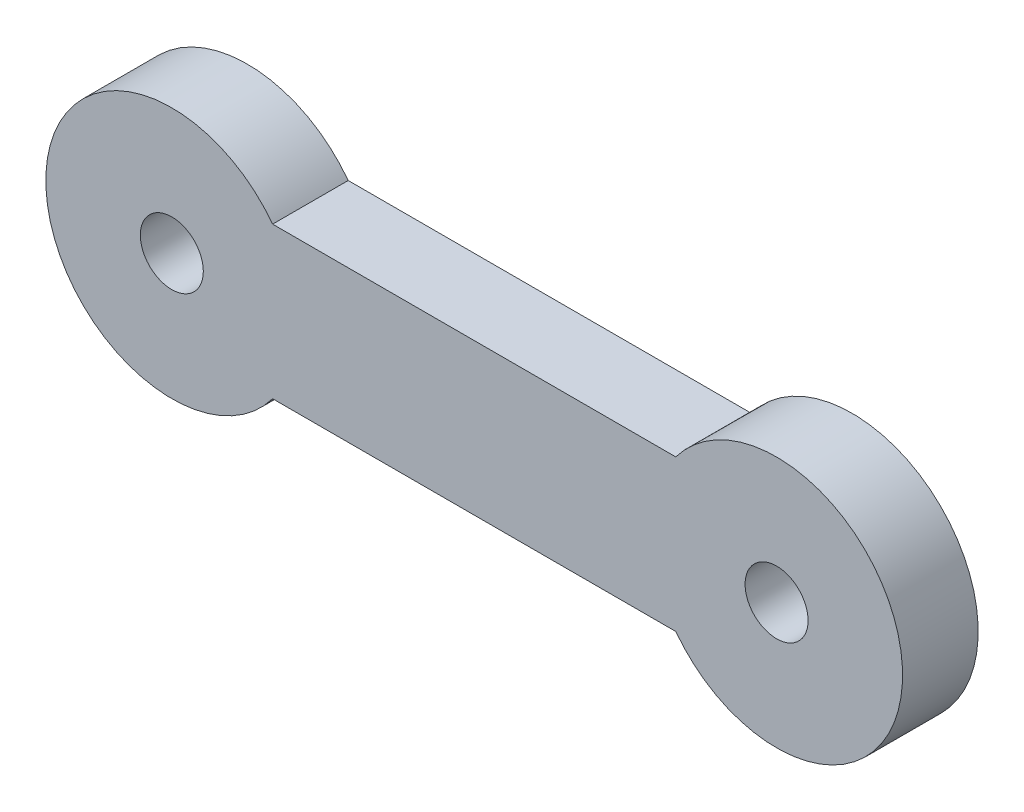
SolidWorks part; units mm, degrees
ref_plane "Front Plane" through (0, 0, 0) normal (0, 0, 1) x (1, 0, 0)
ref_plane "Top Plane" through (0, 0, 0) normal (0, 1, 0) x (1, 0, 0)
ref_plane "Right Plane" through (0, 0, 0) normal (1, 0, 0) x (0, 0, -1)
sketch "Sketch2" plane through (0, 0, 0) normal (0, 0, 1) x (1, 0, 0)
  line L0 (-1.3062, 0) -> (22.6938, 0) construction
  line L1 (2.6938, 3) -> (18.6938, 3)
  line L2 (2.6938, -3) -> (18.6938, -3)
  circle A0 centre (-1.3062, 0) radius 1.25
  circle A1 centre (22.6938, 0) radius 1.25
  arc A2 (2.6938, 3) -> (2.6938, -3) centre (-1.3062, 0) ccw
  arc A3 (18.6938, -3) -> (18.6938, 3) centre (22.6938, 0) ccw
  dimension "D2" = 2.5
  dimension "D3" = 2.5
  dimension "D4" = 10
  dimension "D5" = 10
  dimension "D1" = 24
  dimension "D6" = 3
  dimension "D7" = 3
extrude "Boss-Extrude1" add sketch "Sketch2" along normal blind 3
